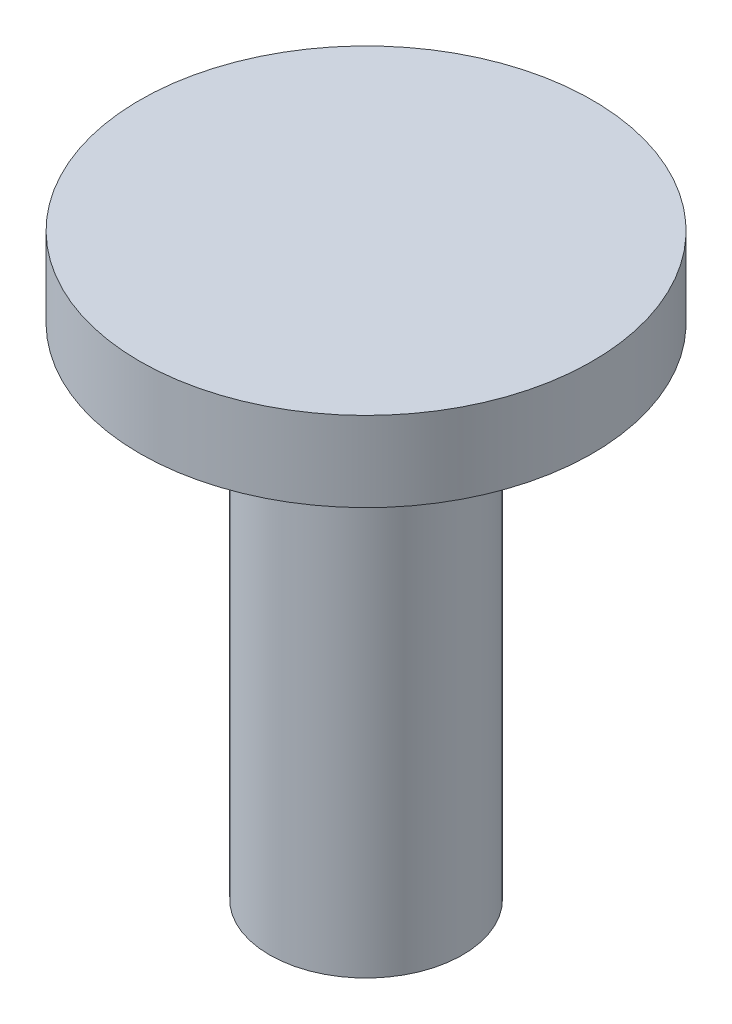
SolidWorks part; units mm, degrees
ref_plane "Front Plane" through (0, 0, 0) normal (0, 0, 1) x (1, 0, 0)
ref_plane "Top Plane" through (0, 0, 0) normal (0, 1, 0) x (1, 0, 0)
ref_plane "Right Plane" through (0, 0, 0) normal (1, 0, 0) x (0, 0, -1)
sketch "Sketch1" plane through (0, 0, 0) normal (0, 1, 0) x (1, 0, 0)
  circle A0 centre (0, 0) radius 1.45
extrude "Boss-Extrude1" add sketch "Sketch1" along normal blind 7.5
sketch "Sketch2" plane through (0, 7.5, 0) normal (0, 1, 0) x (1, 0, 0)
  circle A0 centre (0, 0) radius 3.4
extrude "Boss-Extrude2" add sketch "Sketch2" along normal blind 1.2
